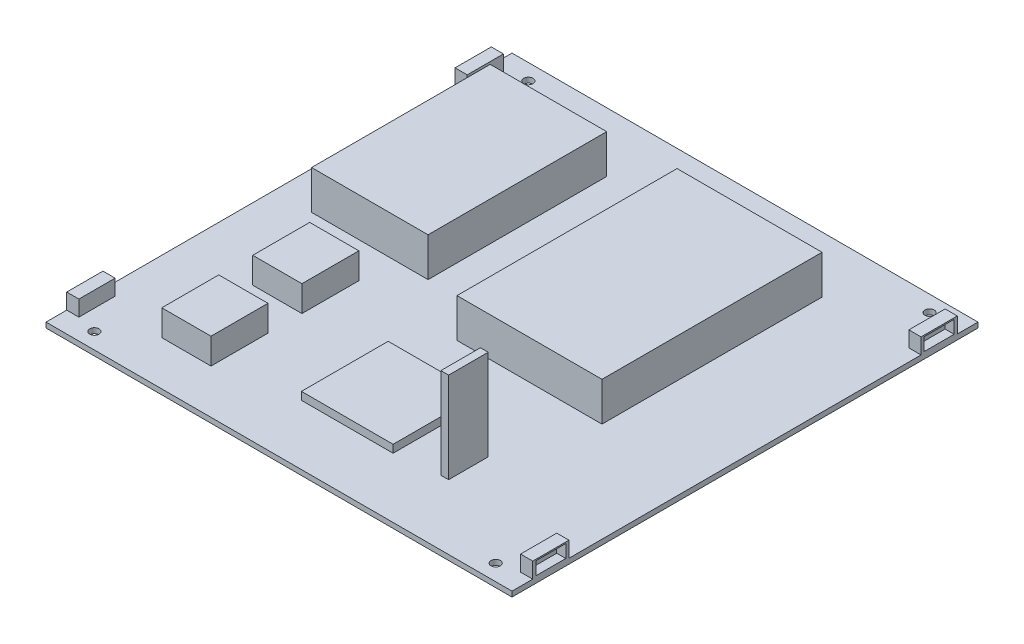
SolidWorks part; units mm, degrees
ref_plane "前视基准面" through (0, 0, 0) normal (0, 0, 1) x (1, 0, 0)
ref_plane "上视基准面" through (0, 0, 0) normal (0, 1, 0) x (1, 0, 0)
ref_plane "右视基准面" through (0, 0, 0) normal (1, 0, 0) x (0, 0, -1)
other "Configuration Table"
sketch "草图1" plane through (0, 0, 0) normal (0, 1, 0) x (1, 0, 0)
  line L1 (90, -90) -> (-90, -90)
  line L2 (90, -90) -> (90, 90)
  line L3 (90, 90) -> (-90, 90)
  line L4 (-90, -90) -> (-90, 90)
  line L5 (90, -90) -> (-90, 90) construction
  line L6 (90, 90) -> (-90, -90) construction
  point P0 (0, 0)
  dimension "D1" = 180
  dimension "D2" = 180
extrude "凸台-拉伸1" add sketch "草图1" along normal blind 2
sketch "草图2" plane through (0, 2, 0) normal (0, 1, 0) x (1, 0, 0)
  line L0 (-90, 82) -> (-90, 68)
  line L1 (-90, 90) -> (-90, -90) construction
  line L2 (-90, 68) -> (-85.3, 68)
  line L3 (-85.3, 68) -> (-85.3, 82)
  line L4 (-85.3, 82) -> (-90, 82)
  line L5 (90, 90) -> (-90, 90) construction
  line L6 (0, 0) -> (0, 135.1735) construction
  line L7 (0, 0) -> (207.6218, 0) construction
  line L8 (-85.3, -82) -> (-90, -82)
  line L9 (-85.3, -68) -> (-85.3, -82)
  line L10 (-90, -68) -> (-85.3, -68)
  line L11 (-90, -82) -> (-90, -68)
  line L12 (90, -82) -> (90, -68)
  line L13 (90, -68) -> (85.3, -68)
  line L14 (85.3, -68) -> (85.3, -82)
  line L15 (85.3, -82) -> (90, -82)
  line L16 (85.3, 82) -> (90, 82)
  line L17 (85.3, 68) -> (85.3, 82)
  line L18 (90, 68) -> (85.3, 68)
  line L19 (90, 82) -> (90, 68)
  dimension "D1" = 14
  dimension "D2" = 4.7
  dimension "D3" = 8
extrude "凸台-拉伸2" add sketch "草图2" along normal blind 6.05
sketch "草图3" plane through (-90, 0, 0) normal (-1, 0, 0) x (0, 0, 1)
  line L2 (-68, 8.05) -> (-82, 2) construction
  line L4 (-69.2149, 2.525) -> (-80.7851, 2.525)
  line L5 (-69.2149, 2.525) -> (-69.2149, 7.525)
  line L6 (-69.2149, 7.525) -> (-80.7851, 7.525)
  line L7 (-80.7851, 2.525) -> (-80.7851, 7.525)
  line L8 (-69.2149, 2.525) -> (-80.7851, 7.525) construction
  line L9 (-69.2149, 7.525) -> (-80.7851, 2.525) construction
  point P7 (-75, 5.025)
  dimension "D1" = 5
extrude "切除-拉伸1" cut sketch "草图3" against normal blind 3.5 contours L5 L4 L7 L6
mirror "镜向1" about plane through (0, 0, 0) normal (1, 0, 0) of "切除-拉伸1" second plane through (0, 0, 0) second plane normal (0, 0, 1)
sketch "草图4" plane through (0, 2, 0) normal (0, 1, 0) x (1, 0, 0)
  line L1 (-30.4158, -2.0078) -> (-75.4158, -2.0078)
  line L2 (-30.4158, -2.0078) -> (-30.4158, 66.9922)
  line L3 (-30.4158, 66.9922) -> (-75.4158, 66.9922)
  line L4 (-75.4158, -2.0078) -> (-75.4158, 66.9922)
  line L5 (-30.4158, -2.0078) -> (-75.4158, 66.9922) construction
  line L6 (-30.4158, 66.9922) -> (-75.4158, -2.0078) construction
  point P0 (-52.9158, 32.4922)
  dimension "D1" = 45
  dimension "D2" = 69
extrude "凸台-拉伸3" add sketch "草图4" along normal blind 15
sketch "草图5" plane through (0, 2, 0) normal (0, 1, 0) x (1, 0, 0)
  line L0 (-75.4158, 14.5346) -> (-30.4158, 14.5346) construction
  line L1 (-43.4158, -37.73) -> (-62.4158, -37.73)
  line L2 (-43.4158, -37.73) -> (-43.4158, -15.73)
  line L3 (-43.4158, -15.73) -> (-62.4158, -15.73)
  line L4 (-62.4158, -37.73) -> (-62.4158, -15.73)
  line L5 (-43.4158, -37.73) -> (-62.4158, -15.73) construction
  line L6 (-43.4158, -15.73) -> (-62.4158, -37.73) construction
  line L11 (-43.4158, -72.8549) -> (-62.4158, -72.8549)
  line L12 (-43.4158, -72.8549) -> (-43.4158, -50.8549)
  line L13 (-43.4158, -50.8549) -> (-62.4158, -50.8549)
  line L14 (-62.4158, -72.8549) -> (-62.4158, -50.8549)
  line L15 (-43.4158, -72.8549) -> (-62.4158, -50.8549) construction
  line L16 (-43.4158, -50.8549) -> (-62.4158, -72.8549) construction
  line L17 (-75.4158, 66.9922) -> (-75.4158, -2.0078) construction
  line L18 (-30.4158, -2.0078) -> (-30.4158, 66.9922) construction
  line L19 (-52.9158, 14.5346) -> (-52.9158, -26.73) construction
  line L20 (-52.9158, -26.73) -> (-52.9158, -61.8549) construction
  point P0 (-52.9158, -26.73)
  point P5 (-52.9158, -61.8549)
  dimension "D1" = 22
  dimension "D2" = 19
  dimension "D3" = 22
  dimension "D4" = 19
extrude "凸台-拉伸4" add sketch "草图5" along normal blind 10
sketch "草图6" plane through (0, 2, 0) normal (0, 1, 0) x (1, 0, 0)
  line L1 (51.5233, -16.7664) -> (-4.4767, -16.7664)
  line L2 (51.5233, -16.7664) -> (51.5233, 68.2336)
  line L3 (51.5233, 68.2336) -> (-4.4767, 68.2336)
  line L4 (-4.4767, -16.7664) -> (-4.4767, 68.2336)
  line L5 (51.5233, -16.7664) -> (-4.4767, 68.2336) construction
  line L6 (51.5233, 68.2336) -> (-4.4767, -16.7664) construction
  point P0 (23.5233, 25.7336)
  dimension "D1" = 85
  dimension "D2" = 56
extrude "凸台-拉伸5" add sketch "草图6" along normal blind 15
sketch "草图7" plane through (0, 2, 0) normal (0, 1, 0) x (1, 0, 0)
  line L1 (27.9118, -73.8434) -> (-7.4882, -73.8434)
  line L2 (27.9118, -73.8434) -> (27.9118, -40.3434)
  line L3 (27.9118, -40.3434) -> (-7.4882, -40.3434)
  line L4 (-7.4882, -73.8434) -> (-7.4882, -40.3434)
  line L5 (27.9118, -73.8434) -> (-7.4882, -40.3434) construction
  line L6 (27.9118, -40.3434) -> (-7.4882, -73.8434) construction
  point P0 (10.2118, -57.0934)
  dimension "D1" = 35.4
  dimension "D2" = 33.5
extrude "凸台-拉伸6" add sketch "草图7" along normal blind 10
sketch "草图8" plane through (0, 0, 73.8434) normal (0, 0, 1) x (1, 0, 0)
  line L0 (-7.4882, 9) -> (27.9118, 9)
  line L1 (-7.4882, 12) -> (-7.4882, 2) construction
  line L2 (27.9118, 12) -> (27.9118, 2) construction
  line L3 (27.9118, 9) -> (27.9118, 2)
  line L4 (27.9118, 2) -> (-7.4882, 2)
  line L5 (-7.4882, 2) -> (-7.4882, 9)
  line L6 (-7.4882, 12) -> (27.9118, 12) construction
  dimension "D1" = 3
extrude "切除-拉伸6" cut sketch "草图8" against normal blind 30
sketch "草图9" plane through (0, 2, 0) normal (0, 1, 0) x (1, 0, 0)
  line L1 (37.4906, -49.6755) -> (40.4906, -49.6755)
  line L2 (37.4906, -49.6755) -> (37.4906, -64.9755)
  line L3 (37.4906, -64.9755) -> (40.4906, -64.9755)
  line L4 (40.4906, -49.6755) -> (40.4906, -64.9755)
  line L5 (37.4906, -49.6755) -> (40.4906, -64.9755) construction
  line L6 (37.4906, -64.9755) -> (40.4906, -49.6755) construction
  point P0 (38.9906, -57.3255)
  dimension "D1" = 15.3
  dimension "D2" = 3
extrude "凸台-拉伸7" add sketch "草图9" along normal blind 35
sketch "草图10" plane through (0, 2, 0) normal (0, 1, 0) x (1, 0, 0)
  circle A0 centre (77.5, 83.8022) radius 1.8
  dimension "D1" = 3.6
  dimension "D2" = 77.5
extrude "切除-拉伸7" cut sketch "草图10" against normal blind 10
mirror "镜向3" about plane through (0, 0, 0) normal (1, 0, 0) of "切除-拉伸7" second plane through (0, 0, 0) second plane normal (0, 0, 1)
